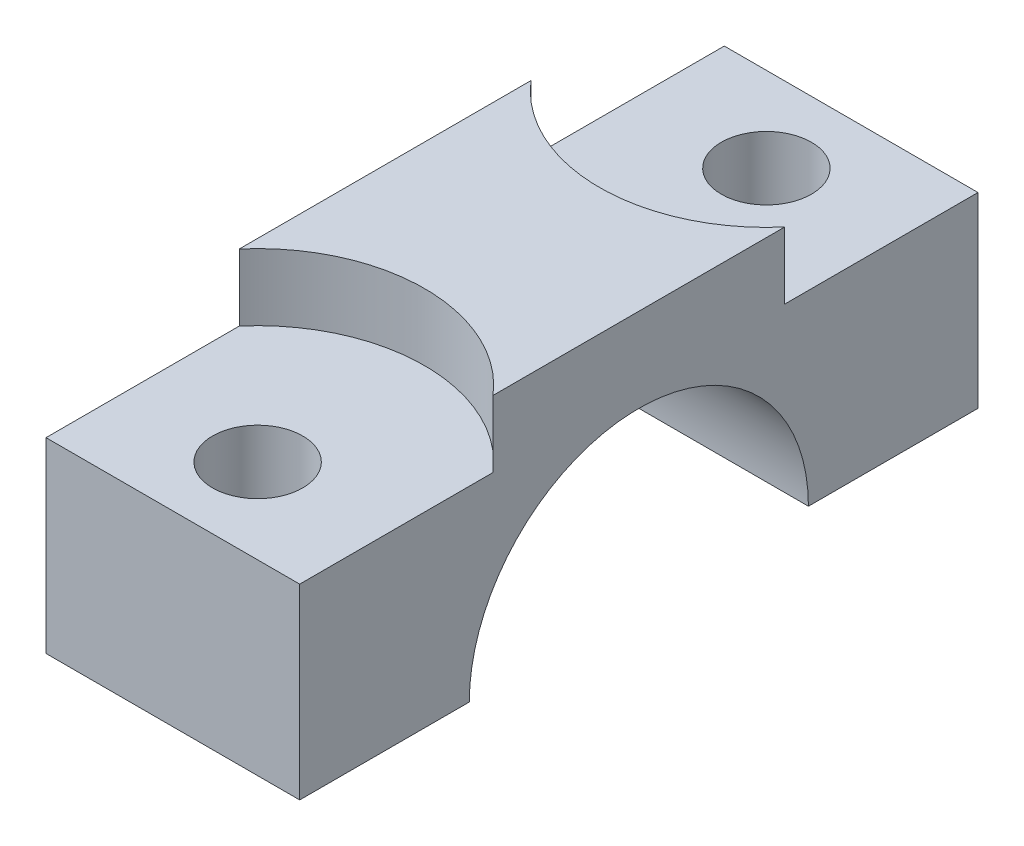
SolidWorks part; units mm, degrees
ref_plane "Front Plane" through (0, 0, 0) normal (0, 0, 1) x (1, 0, 0)
ref_plane "Top Plane" through (0, 0, 0) normal (0, 1, 0) x (1, 0, 0)
ref_plane "Right Plane" through (0, 0, 0) normal (1, 0, 0) x (0, 0, -1)
sketch "Sketch1" plane through (0, 0, 0) normal (1, 0, 0) x (0, 0, -1)
  line L1 (-25.4, 0) -> (25.4, 0)
  line L2 (-25.4, 0) -> (-25.4, 19)
  line L3 (-25.4, 19) -> (25.4, 19)
  line L4 (25.4, 0) -> (25.4, 19)
  circle A0 centre (0, 0) radius 12.7
  point P7 (0, 0)
  point P8 (0, 0)
  dimension "D1" = 19
  dimension "D3" = 25.4
  dimension "D2" = 50.8
extrude "Boss-Extrude1" add sketch "Sketch1" along normal mid plane 19 contours A0 L1 L4 L3 L2
sketch "Sketch2" plane through (0, 0, 0) normal (0, -1, 0) x (1, 0, 0)
  line L0 (0, 25.4) -> (0, 12.7) construction
  line L1 (9.5, 25.4) -> (-9.5, 25.4) construction
  line L2 (9.5, 12.7) -> (-9.5, 12.7) construction
  line L3 (0, -12.7) -> (0, -25.4) construction
  line L4 (9.5, -12.7) -> (-9.5, -12.7) construction
  line L5 (9.5, -25.4) -> (-9.5, -25.4) construction
  point P12 (0, 19.05)
  point P13 (0, -19.05)
hole_wizard "CBORE for M12 Hex Head Cap Screw1" positions "Sketch3" profile "Sketch4" counterbore size "M12" standard "ISO" end condition through all
sketch "Sketch3" plane through (0, 19, 0) normal (0, 1, 0) x (1, 0, 0)
  point P0 (0, 19.05)
  point P3 (0, -19.05)
sketch "Sketch4" plane through (0, 19, -19.05) normal (1, 0, 0) x (0, 0, 1)
  line L0 (0, 0) -> (0, 19)
  line L1 (0, 19) -> (3.375, 19)
  line L3 (3.375, 19) -> (3.375, 5)
  line L4 (3.375, 5) -> (12.5, 5)
  line L5 (12.5, 5) -> (12.5, 0)
  line L7 (12.5, 0) -> (0, 0)
  line L11 (0, -6.35) -> (0, 107.95) construction
  dimension "Thru Hole Dia." = 6.75
  dimension "Thru Hole Depth" = 19
  dimension "C'Bore Dia." = 25
  dimension "C'Bore Depth" = 5
